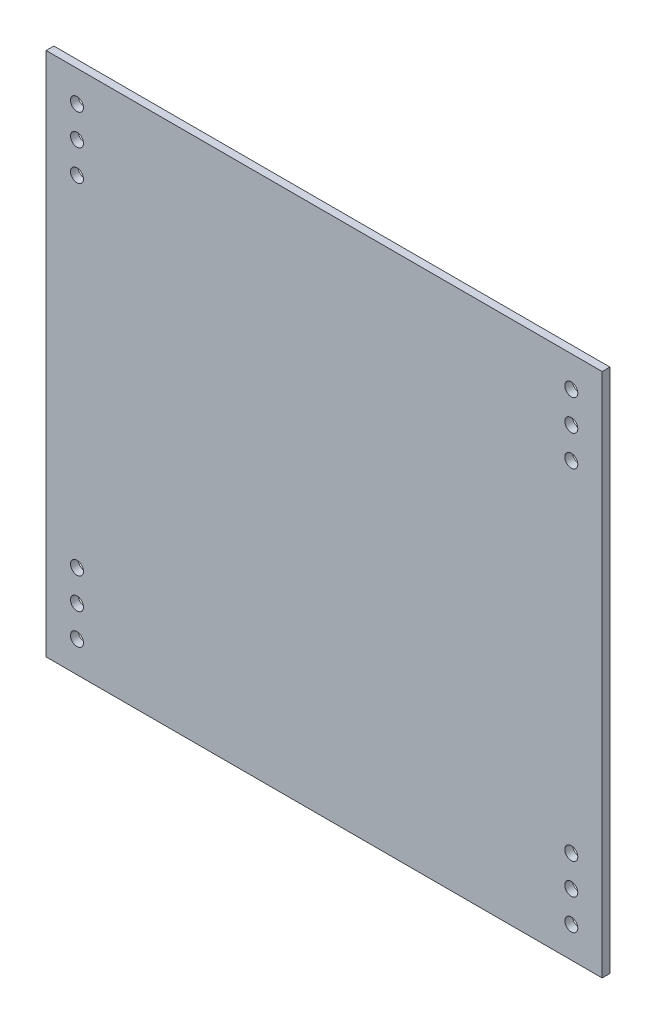
SolidWorks part; units mm, degrees
ref_plane "Front Plane" through (0, 0, 0) normal (0, 0, 1) x (1, 0, 0)
ref_plane "Top Plane" through (0, 0, 0) normal (0, 1, 0) x (1, 0, 0)
ref_plane "Right Plane" through (0, 0, 0) normal (1, 0, 0) x (0, 0, -1)
sketch "Sketch1" plane through (0, 0, 0) normal (0, 0, 1) x (1, 0, 0)
  line L1 (-114.3, 107.95) -> (114.3, 107.95)
  line L2 (-114.3, 107.95) -> (-114.3, -107.95)
  line L3 (-114.3, -107.95) -> (114.3, -107.95)
  line L4 (114.3, 107.95) -> (114.3, -107.95)
  line L5 (-114.3, 107.95) -> (114.3, -107.95) construction
  line L6 (-114.3, -107.95) -> (114.3, 107.95) construction
  point P0 (0, 0)
extrude "Boss-Extrude1" add sketch "Sketch1" along normal blind 3.175
sketch "Sketch2" plane through (0, 0, 3.175) normal (0, 0, 1) x (1, 0, 0)
  line L0 (-114.3, -107.95) -> (-101.6, -107.95) construction
  line L1 (-114.3, -107.95) -> (114.3, -107.95) construction
  line L2 (-101.6, -107.95) -> (-101.6, -95.25) construction
  line L3 (-101.6, -95.25) -> (-101.6, -82.55) construction
  line L4 (-101.6, -82.55) -> (-101.6, -69.85) construction
  line L5 (0, -107.95) -> (0, 107.95) construction
  line L6 (114.3, 107.95) -> (-114.3, 107.95) construction
  line L7 (-115.3889, 0) -> (114.3, 0) construction
  line L8 (114.3, -107.95) -> (114.3, 107.95) construction
  circle A0 centre (-101.6, -69.85) radius 2.667
  circle A1 centre (-101.6, -82.55) radius 2.667
  circle A2 centre (-101.6, -95.25) radius 2.667
  circle A3 centre (-101.6, 95.25) radius 2.667
  circle A4 centre (-101.6, 82.55) radius 2.667
  circle A5 centre (-101.6, 69.85) radius 2.667
  circle A6 centre (101.6, 95.25) radius 2.667
  circle A7 centre (101.6, 82.55) radius 2.667
  circle A8 centre (101.6, 69.85) radius 2.667
  circle A9 centre (101.6, -95.25) radius 2.667
  circle A10 centre (101.6, -82.55) radius 2.667
  circle A11 centre (101.6, -69.85) radius 2.667
extrude "Cut-Extrude1" cut sketch "Sketch2" against normal blind 3.175
